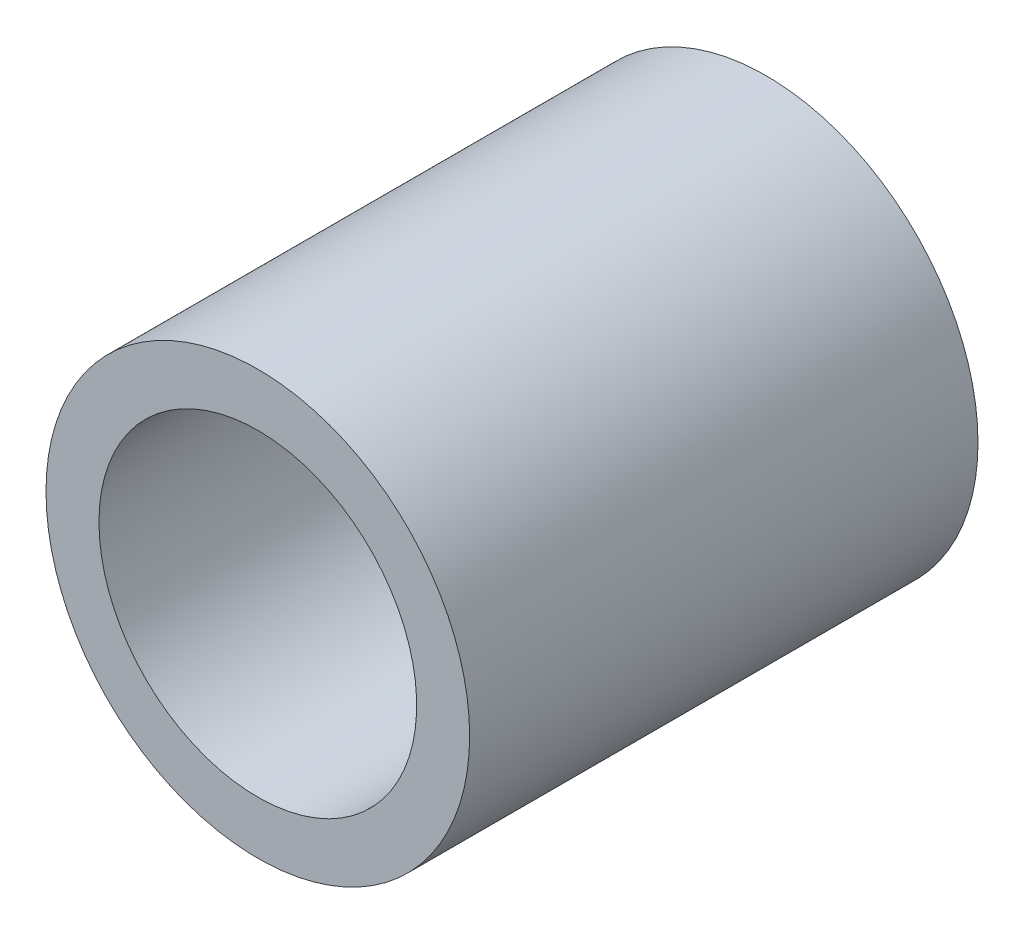
SolidWorks part; units mm, degrees
ref_plane "Front Plane" through (0, 0, 0) normal (0, 0, 1) x (1, 0, 0)
ref_plane "Top Plane" through (0, 0, 0) normal (0, 1, 0) x (1, 0, 0)
ref_plane "Right Plane" through (0, 0, 0) normal (1, 0, 0) x (0, 0, -1)
sketch "Sketch1" plane through (0, 0, 0) normal (0, 0, 1) x (1, 0, 0)
  circle A0 centre (0, 0) radius 2.54
  circle A1 centre (0, 0) radius 1.905
  dimension "D1" = 3.81
  dimension "D2" = 5.08
extrude "Boss-Extrude1" add sketch "Sketch1" along normal blind 6.096
